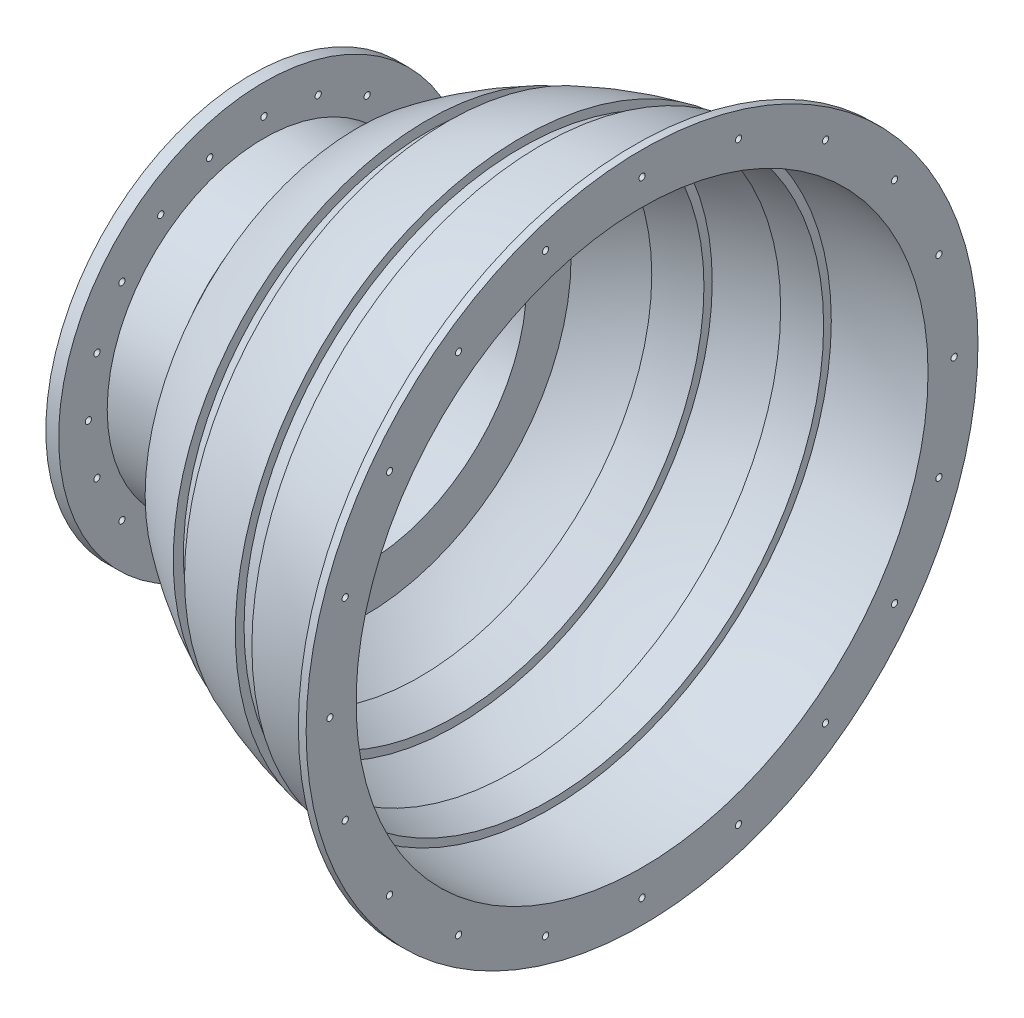
SolidWorks part; units mm, degrees
ref_plane "Front Plane" through (0, 0, 0) normal (0, 0, 1) x (1, 0, 0)
ref_plane "Top Plane" through (0, 0, 0) normal (0, 1, 0) x (1, 0, 0)
ref_plane "Right Plane" through (0, 0, 0) normal (1, 0, 0) x (0, 0, -1)
sketch "Sketch1" plane through (0, 0, 0) normal (0, 0, 1) x (1, 0, 0)
  line L0 (149.3919, 0) -> (-149.3919, 0) construction
  line L2 (-125.25, 131.5647) -> (-117.0287, 131.5647)
  line L3 (-125.25, 95.4355) -> (-81.6676, 95.4355)
  line L4 (-125.25, 95.4355) -> (-125.25, 131.5647)
  line L5 (-81.6676, 95.4355) -> (-52.3185, 103.5318)
  line L6 (-117.0287, 131.5647) -> (-117.0287, 100.4355)
  line L7 (-117.0287, 100.4355) -> (-82.6194, 100.4355)
  line L8 (-82.6194, 100.4355) -> (-57.3185, 107.4151)
  line L12 (-52.3185, 103.5318) -> (-52.3185, 132.0558)
  line L15 (125.25, 215.2556) -> (120.25, 215.2556)
  line L16 (125.25, 183.2556) -> (125.25, 215.2556)
  line L17 (120.25, 215.2556) -> (120.25, 188.2556)
  line L18 (-57.3185, 135.8568) -> (-57.3185, 107.4151)
  line L20 (-17.3185, 148.7857) -> (5.8039, 159.1057)
  line L21 (-17.3185, 148.7857) -> (-17.3185, 153.7857)
  line L22 (5.8039, 164.4252) -> (5.8039, 159.1057)
  line L23 (0.6815, 168.6011) -> (0.6815, 162.2949)
  line L25 (-12.3185, 156.3147) -> (-12.3185, 162.8528)
  line L26 (60.6815, 185.4595) -> (60.6815, 180.0388)
  line L27 (42.6815, 176.2982) -> (42.6815, 171.3782)
  line L28 (42.6815, 171.3782) -> (65.6662, 175.9286)
  line L30 (65.6662, 180.8494) -> (65.6662, 175.9286)
  line L31 (47.6815, 177.4668) -> (47.6815, 183.0609)
  arc A0 (-52.3185, 132.0558) -> (-17.3185, 153.7857) centre (106.2118, -84.2342) cw
  arc A1 (-57.3185, 135.8568) -> (-12.3185, 162.8528) centre (103.0104, -80.3935) cw
  arc A2 (-12.3185, 156.3147) -> (0.6815, 162.2949) centre (106.2118, -84.2342) cw
  arc A3 (5.8039, 164.4252) -> (42.6815, 176.2982) centre (106.2118, -84.2342) cw
  arc A4 (0.6815, 168.6011) -> (47.6815, 183.0609) centre (103.0104, -80.3935) cw
  arc A5 (47.6815, 177.4668) -> (60.6815, 180.0388) centre (106.2118, -84.2342) cw
  arc A6 (65.6662, 180.8494) -> (125.25, 183.2556) centre (106.2118, -84.2342) cw
  arc A7 (60.6815, 185.4595) -> (120.25, 188.2556) centre (103.0104, -80.3935) cw
  point P4 (0, 0)
  point P6 (0, 0)
  dimension "D1" = 250.5
  dimension "D2" = 5
  dimension "D3" = 32
  dimension "D4" = 5
  dimension "D5" = 27
  dimension "D6" = 5
  dimension "D7" = 5
revolve "Revolve1" add sketch "Sketch1" angle 360 about L0
sketch "Sketch2" plane through (-125.25, 0, 0) normal (-1, 0, 0) x (0, 0, 1)
  circle A0 centre (0, 112.5) radius 2
  dimension "D1" = 4
  dimension "D2" = 112.5
extrude "Cut-Extrude1" cut sketch "Sketch2" against normal blind 10
sketch "Sketch4" plane through (120.25, 0, 0) normal (-1, 0, 0) x (0, 0, 1)
  circle A0 centre (0, 200) radius 2
  dimension "D1" = 4
  dimension "D2" = 200
extrude "Cut-Extrude2" cut sketch "Sketch4" against normal blind 10
pattern_circular "CirPattern1" count 20 over 360 about axis through (0, 0, 0) along (1, 0, 0) of "Cut-Extrude2", "Cut-Extrude1"
